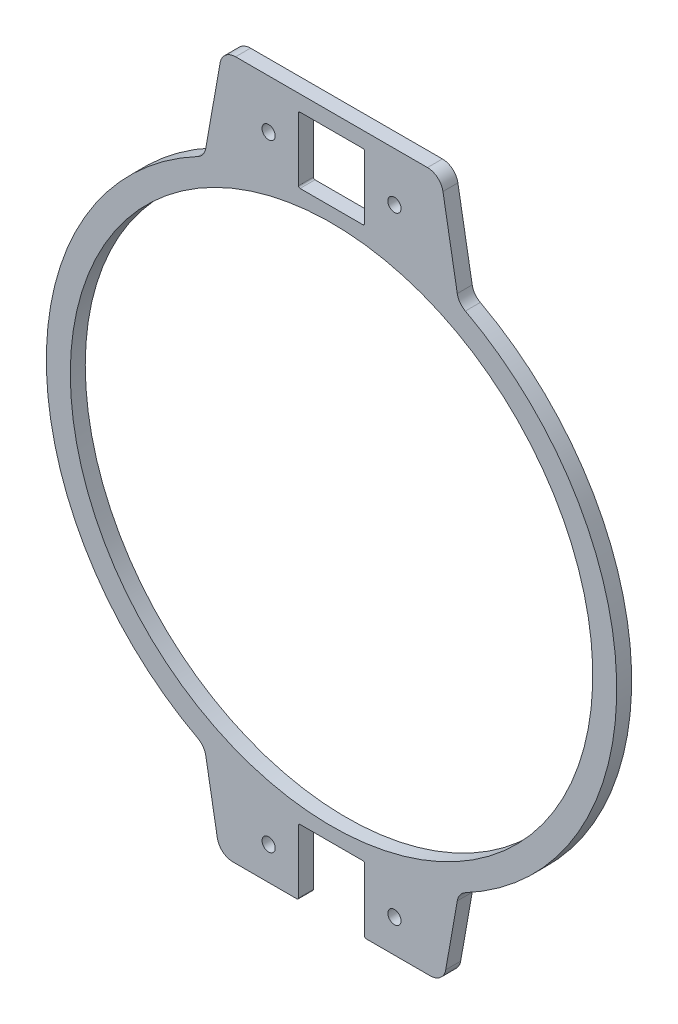
SolidWorks part; units mm, degrees
material "6061-T6 (SS)"
ref_plane "Front Plane" through (0, 0, 0) normal (0, 0, 1) x (1, 0, 0)
ref_plane "Top Plane" through (0, 0, 0) normal (0, 1, 0) x (1, 0, 0)
ref_plane "Right Plane" through (0, 0, 0) normal (1, 0, 0) x (0, 0, -1)
sketch "Sketch2" plane through (0, 0, 109.855) normal (0, 0, -1) x (-1, 0, 0)
  line L0 (-31.3816, -108.55) -> (31.3816, -108.55) construction
  line L1 (36.3057, -104.4182) -> (41.8173, -73.1605) construction
  line L2 (-41.8173, -73.1605) -> (-36.3057, -104.4182) construction
  line L3 (41.8173, 73.1605) -> (35.424, 109.4182) construction
  line L4 (30.5, 113.55) -> (-30.5, 113.55) construction
  line L5 (-35.424, 109.4182) -> (-41.8173, 73.1605) construction
  line L6 (-31.3816, -108.55) -> (-11, -108.55)
  line L7 (36.3057, -104.4182) -> (39.9744, -83.6118)
  line L8 (-39.9744, -83.6118) -> (-36.3057, -104.4182)
  line L9 (39.9744, 83.6118) -> (35.424, 109.4182)
  line L10 (30.5, 113.55) -> (-30.5, 113.55)
  line L11 (-35.424, 109.4182) -> (-39.9744, 83.6118)
  line L12 (10, 87.55) -> (-10, 87.55) construction
  line L13 (10.5, 108.05) -> (10.5, 88.05) construction
  line L14 (-10, 108.55) -> (10, 108.55) construction
  line L15 (-10.5, 88.05) -> (-10.5, 108.05) construction
  line L16 (10, 87.55) -> (-10, 87.55)
  line L17 (10.5, 108.05) -> (10.5, 88.05)
  line L18 (-10, 108.55) -> (10, 108.55)
  line L19 (-10.5, 88.05) -> (-10.5, 108.05)
  line L20 (10.5, -88.05) -> (10.5, -108.05) construction
  line L21 (-10, -87.55) -> (10, -87.55) construction
  line L22 (-10.5, -108.05) -> (-10.5, -88.05) construction
  line L23 (10.5, -88.05) -> (10.5, -108.05)
  line L24 (-10, -87.55) -> (10, -87.55)
  line L25 (-10.5, -108.05) -> (-10.5, -88.05)
  line L26 (11, -108.55) -> (31.3816, -108.55)
  arc A0 (-36.3057, -104.4182) -> (-31.3816, -108.55) centre (-31.3816, -103.55) ccw construction
  arc A1 (31.3816, -108.55) -> (36.3057, -104.4182) centre (31.3816, -103.55) ccw construction
  arc A14 (35.424, 109.4182) -> (30.5, 113.55) centre (30.5, 108.55) ccw construction
  arc A15 (-30.5, 113.55) -> (-35.424, 109.4182) centre (-30.5, 108.55) ccw construction
  arc A18 (-36.3057, -104.4182) -> (-31.3816, -108.55) centre (-31.3816, -103.55) ccw
  arc A19 (31.3816, -108.55) -> (36.3057, -104.4182) centre (31.3816, -103.55) ccw
  arc A32 (35.424, 109.4182) -> (30.5, 113.55) centre (30.5, 108.55) ccw
  arc A33 (-30.5, 113.55) -> (-35.424, 109.4182) centre (-30.5, 108.55) ccw
  circle A36 centre (-20, 98.05) radius 2.1 construction
  circle A37 centre (20, 98.05) radius 2.1 construction
  circle A38 centre (20, -98.05) radius 2.1 construction
  circle A39 centre (-20, -98.05) radius 2.1 construction
  circle A40 centre (-20, 98.05) radius 2.1 construction
  circle A41 centre (20, 98.05) radius 2.1 construction
  circle A42 centre (20, -98.05) radius 2.1 construction
  circle A43 centre (-20, -98.05) radius 2.1 construction
  arc A44 (-10.5, 88.05) -> (-10, 87.55) centre (-10, 88.05) ccw construction
  arc A45 (10, 87.55) -> (10.5, 88.05) centre (10, 88.05) ccw construction
  arc A46 (10.5, 108.05) -> (10, 108.55) centre (10, 108.05) ccw construction
  arc A47 (-10, 108.55) -> (-10.5, 108.05) centre (-10, 108.05) ccw construction
  arc A48 (-10.5, 88.05) -> (-10, 87.55) centre (-10, 88.05) ccw
  arc A49 (10, 87.55) -> (10.5, 88.05) centre (10, 88.05) ccw
  arc A50 (10.5, 108.05) -> (10, 108.55) centre (10, 108.05) ccw
  arc A51 (-10, 108.55) -> (-10.5, 108.05) centre (-10, 108.05) ccw
  arc A52 (10.5, -88.05) -> (10, -87.55) centre (10, -88.05) ccw construction
  arc A53 (-10, -87.55) -> (-10.5, -88.05) centre (-10, -88.05) ccw construction
  arc A54 (10.5, -88.05) -> (10, -87.55) centre (10, -88.05) ccw
  arc A55 (-10, -87.55) -> (-10.5, -88.05) centre (-10, -88.05) ccw
  arc A56 (-11, -108.55) -> (-10.5, -108.05) centre (-11, -108.05) ccw
  arc A57 (10.5, -108.05) -> (11, -108.55) centre (11, -108.05) ccw
  circle A58 centre (0, 0) radius 82.55 construction
  circle A59 centre (0, 0) radius 83.05
  arc A60 (42.5519, -80.0649) -> (42.5519, 80.0649) centre (0, 0) ccw
  arc A61 (-42.5519, 80.0649) -> (-42.5519, -80.0649) centre (0, 0) ccw
  arc A62 (39.9744, -83.6118) -> (42.5519, -80.0649) centre (44.8984, -84.48) cw
  arc A63 (-39.9744, -83.6118) -> (-42.5519, -80.0649) centre (-44.8984, -84.48) ccw
  arc A64 (39.9744, 83.6118) -> (42.5519, 80.0649) centre (44.8984, 84.48) ccw
  arc A65 (-39.9744, 83.6118) -> (-42.5519, 80.0649) centre (-44.8984, 84.48) cw
  circle A66 centre (20, 98.05) radius 2.75
  circle A67 centre (-20, 98.05) radius 2.75
  circle A68 centre (20, -98.05) radius 2.75
  circle A69 centre (-20, -98.05) radius 2.75
  point P44 (-40.4051, 81.1695)
  dimension "D1" = 165.1
  dimension "D2" = 0.5
  dimension "D3" = 7.62
  dimension "D4" = 5.5
extrude "Boss-Extrude1" add sketch "Sketch2" along normal blind 4.7498
sketch "Sketch3" plane through (0, 0, 109.855) normal (0, 0, 1) x (1, 0, 0)
  circle A9 centre (-20, 98.05) radius 2.1
  circle A10 centre (20, 98.05) radius 2.1
  circle A11 centre (-20, -98.05) radius 2.1
  circle A12 centre (20, -98.05) radius 2.1
  circle A13 centre (-20, 98.05) radius 2.75 construction
  circle A14 centre (20, 98.05) radius 2.75 construction
  circle A15 centre (20, -98.05) radius 2.75 construction
  circle A16 centre (-20, -98.05) radius 2.75 construction
  circle A17 centre (-20, 98.05) radius 2.75
  circle A18 centre (20, 98.05) radius 2.75
  circle A19 centre (20, -98.05) radius 2.75
  circle A20 centre (-20, -98.05) radius 2.75
  dimension "D1" = 4.2
extrude "Boss-Extrude2" add sketch "Sketch3" against normal up to surface (4.7498 mm away) up to face at (-22.75, -98.05, 105.1052)
